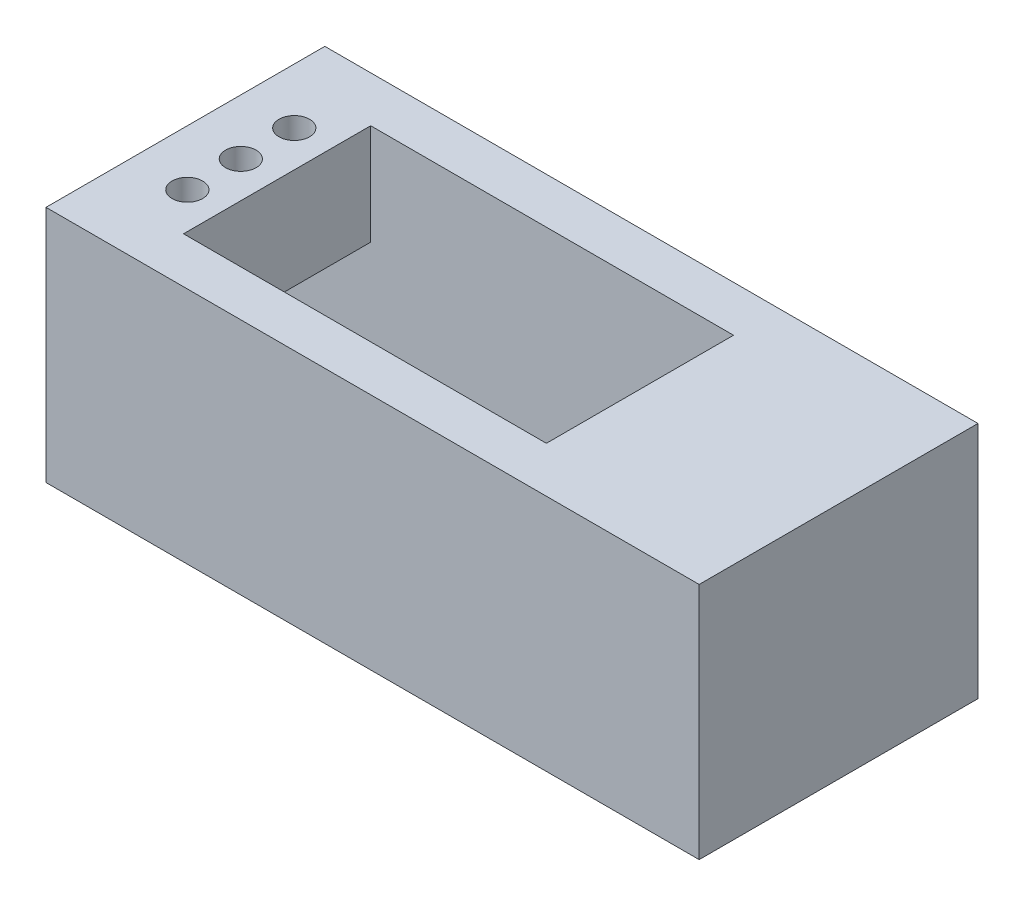
SolidWorks part; units mm, degrees
material "ABS"
ref_plane "Front" through (0, 0, 0) normal (0, 0, 1) x (1, 0, 0)
ref_plane "Top" through (0, 0, 0) normal (0, 1, 0) x (1, 0, 0)
ref_plane "Right" through (0, 0, 0) normal (1, 0, 0) x (0, 0, -1)
sketch "Sketch1" plane through (0, 0, 0) normal (0, 1, 0) x (1, 0, 0)
  line L0 (17.875, -9.125) -> (24.875, -9.125)
  line L1 (-11.875, -6.125) -> (11.875, -6.125)
  line L2 (-11.875, -6.125) -> (-11.875, 6.125)
  line L3 (-11.875, 6.125) -> (11.875, 6.125)
  line L4 (11.875, -6.125) -> (11.875, 6.125)
  line L5 (-11.875, -6.125) -> (11.875, 6.125) construction
  line L6 (-11.875, 6.125) -> (11.875, -6.125) construction
  line L7 (-17.875, 9.125) -> (17.875, 9.125)
  line L8 (-17.875, 9.125) -> (-17.875, -9.125)
  line L9 (-17.875, -9.125) -> (17.875, -9.125)
  line L10 (17.875, 9.125) -> (17.875, -9.125) construction
  line L11 (-17.875, 9.125) -> (17.875, -9.125) construction
  line L12 (-17.875, -9.125) -> (17.875, 9.125) construction
  line L13 (24.875, -9.125) -> (24.875, 9.125)
  line L14 (24.875, 9.125) -> (17.875, 9.125)
  point P0 (0, 0)
  point P6 (0, 0)
  dimension "D1" = 23.75
  dimension "D2" = 12.25
  dimension "D3" = 6
  dimension "D4" = 3
  dimension "7" = 7
extrude "Boss-Extrude1" add sketch "Sketch1" along normal blind 15.6
sketch "Sketch2" plane through (-17.875, 0, 0) normal (-1, 0, 0) x (0, 0, 1)
  line L0 (-9.125, 0) -> (9.125, 0) construction
  line L1 (-6.125, 0) -> (6.125, 0)
  line L2 (-6.125, 0) -> (-6.125, 9)
  line L3 (-6.125, 9) -> (6.125, 9)
  line L4 (6.125, 0) -> (6.125, 9)
  line L7 (6.125, 0) -> (9.125, 0)
  line L8 (-6.125, 0) -> (-9.125, 0) construction
  dimension "D1" = 9
  dimension "D4" = 12.25
extrude "Cut-Extrude1" cut sketch "Sketch2" against normal blind 10 contours L1 L2 L3 L4
sketch "Sketch3" plane through (0, 15.6, 0) normal (0, 1, 0) x (1, 0, 0)
  line L0 (24.875, 9.125) -> (-17.875, 9.125) construction
  line L1 (-17.875, 9.125) -> (-17.875, -9.125) construction
  circle A0 centre (-14.245, 3.495) radius 1
  circle A1 centre (-14.245, -0.005) radius 1
  circle A2 centre (-14.245, -3.505) radius 1
  dimension "D1" = 2
  dimension "D2" = 3.5
  dimension "D3" = 3.5
  dimension "D4" = 5.63
  dimension "D5" = 3.63
extrude "Cut-Extrude2" cut sketch "Sketch3" against normal blind 3
